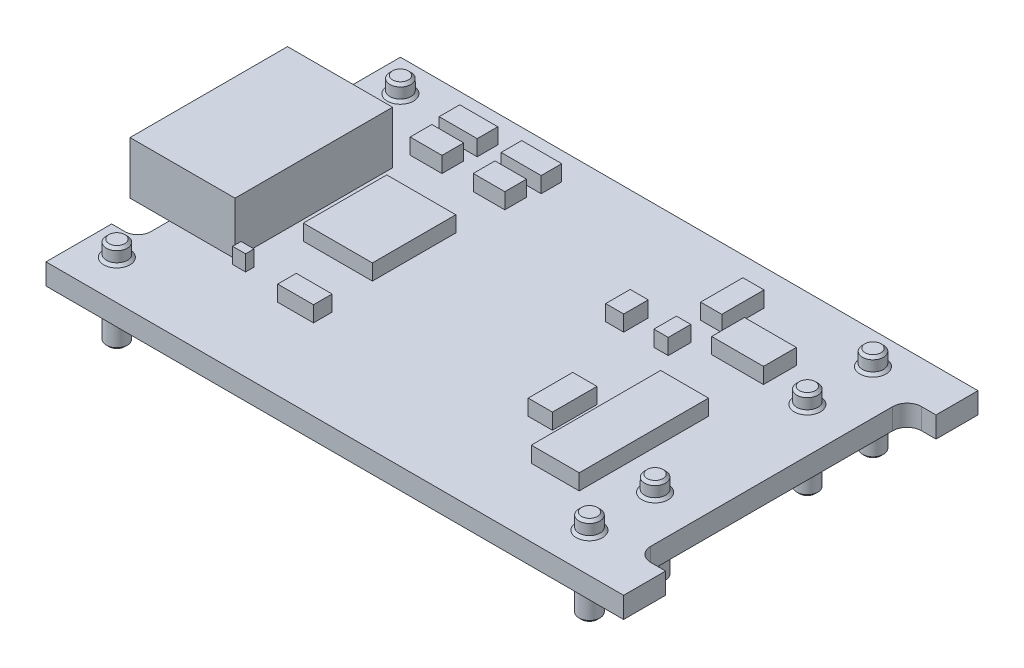
SolidWorks part; units mm, degrees
ref_plane "Front Plane" through (0, 0, 0) normal (0, 0, 1) x (1, 0, 0)
ref_plane "Top Plane" through (0, 0, 0) normal (0, 1, 0) x (1, 0, 0)
ref_plane "Right Plane" through (0, 0, 0) normal (1, 0, 0) x (0, 0, -1)
sketch "Sketch1" plane through (0, 0, 0) normal (0, 1, 0) x (1, 0, 0)
  line L1 (0, 0) -> (27.94, 0)
  line L2 (0, 0) -> (0, 17.145)
  line L3 (0, 17.145) -> (27.94, 17.145)
  line L4 (27.94, 0) -> (27.94, 17.145)
  line L5 (13.97, 17.145) -> (13.97, 0) construction
  line L6 (0, 8.5725) -> (27.94, 8.5725) construction
  point P88 (13.97, 8.5725)
  dimension "D1" = 17.145
  dimension "D2" = 27.94
extrude "Boss-Extrude1" add sketch "Sketch1" along normal blind 1.016
sketch "Sketch2" plane through (0, 1.016, 0) normal (0, 1, 0) x (1, 0, 0)
  line L0 (27.94, 17.145) -> (27.94, 15.113)
  line L1 (27.94, 0) -> (27.94, 17.145) construction
  line L2 (27.94, 0) -> (27.94, 2.032)
  line L3 (0, 17.145) -> (0, 13.843)
  line L4 (27.94, 2.032) -> (26.543, 2.032)
  line L5 (27.94, 2.032) -> (27.94, 15.113)
  line L6 (27.94, 15.113) -> (26.543, 15.113)
  line L7 (26.543, 2.032) -> (26.543, 15.113)
  line L8 (27.2415, 15.113) -> (27.2415, 2.032) construction
  line L9 (27.94, 8.5725) -> (26.543, 8.5725) construction
  line L10 (0, 17.145) -> (0, 0) construction
  line L11 (0, 0) -> (0, 3.302)
  line L13 (0, 13.843) -> (1.27, 13.843)
  line L14 (0, 13.843) -> (0, 3.175)
  line L15 (0, 3.175) -> (1.27, 3.175)
  line L16 (1.27, 13.843) -> (1.27, 3.175)
  line L17 (0.635, 3.175) -> (0.635, 13.843) construction
  line L18 (0, 8.509) -> (1.27, 8.509) construction
  arc A0 (27.2415, 15.113) -> (26.543, 14.4145) centre (27.2415, 14.4145) ccw
  arc A1 (27.2415, 2.032) -> (26.543, 2.6934) centre (27.2229, 2.7119) cw
  arc A2 (0.6501, 13.843) -> (1.27, 13.196) centre (0.6365, 13.2095) cw
  arc A3 (1.27, 3.7929) -> (0.635, 3.175) centre (0.6435, 3.8015) cw
  point P130 (0.635, 8.509)
  point P187 (27.2415, 8.5725)
  line M3 (0, 17.145) -> (0, 0)
  line M5 (27.94, 0) -> (27.94, 17.145)
  dimension "D4" = 3.302
  dimension "D1" = 2.032
  dimension "D2" = 2.032
  dimension "D3" = 1.397
  dimension "D5" = 3.302
  dimension "D6" = 10.668
  dimension "D7" = 1.27
extrude "Cut-Extrude1" cut sketch "Sketch2" against normal blind 1.016 contours A3 L16 A2 L13 L15 M3 | A1 L4 L6 A0 L7 M5
sketch "Sketch3" plane through (0, 1.016, 0) normal (0, 1, 0) x (1, 0, 0)
  line L0 (24.384, 15.621) -> (24.384, 12.446)
  line L1 (0, 17.145) -> (3.048, 17.145)
  line L2 (0, 17.145) -> (0, 14.097)
  line L3 (0, 14.097) -> (3.048, 14.097)
  line L4 (3.048, 17.145) -> (3.048, 14.097)
  line L5 (1.524, 14.097) -> (1.524, 17.145) construction
  line L6 (0, 15.621) -> (3.048, 15.621) construction
  line L7 (0, 0) -> (3.048, 0)
  line L8 (0, 0) -> (0, 3.81)
  line L9 (0, 3.81) -> (3.048, 3.81)
  line L10 (3.048, 0) -> (3.048, 3.81)
  line L11 (1.524, 3.81) -> (1.524, 0) construction
  line L12 (0, 1.905) -> (3.048, 1.905) construction
  line L13 (27.94, 17.145) -> (24.384, 17.145)
  line L14 (27.94, 17.145) -> (27.94, 15.621)
  line L15 (27.94, 15.621) -> (24.384, 15.621)
  line L16 (24.384, 17.145) -> (24.384, 15.621)
  line L17 (26.162, 15.621) -> (26.162, 17.145) construction
  line L18 (27.94, 16.383) -> (24.384, 16.383) construction
  line L19 (24.384, 1.905) -> (24.384, 5.08)
  line L20 (27.94, 0) -> (24.384, 0)
  line L21 (27.94, 0) -> (27.94, 1.905)
  line L22 (27.94, 1.905) -> (24.384, 1.905)
  line L23 (24.384, 0) -> (24.384, 1.905)
  line L24 (26.162, 1.905) -> (26.162, 0) construction
  line L25 (27.94, 0.9525) -> (24.384, 0.9525) construction
  circle A0 centre (1.524, 15.621) radius 0.508
  circle A1 centre (1.524, 1.905) radius 0.508
  circle A2 centre (24.384, 15.621) radius 0.508
  circle A3 centre (24.384, 12.446) radius 0.508
  circle A4 centre (24.384, 1.905) radius 0.508
  circle A5 centre (24.384, 5.08) radius 0.508
  point P89 (26.162, 0.9525)
  point P112 (26.162, 16.383)
  point P188 (1.524, 1.905)
  point P260 (1.524, 15.621)
  dimension "D1" = 1.016
  dimension "D3" = 1.016
  dimension "D6" = 1.016
  dimension "D8" = 1.016
  dimension "D11" = 1.016
  dimension "D13" = 1.016
  dimension "D2" = 3.81
  dimension "D4" = 1.524
  dimension "D5" = 3.556
  dimension "D7" = 3.175
  dimension "D9" = 1.905
  dimension "D10" = 3.556
  dimension "D12" = 3.175
extrude "Boss-Extrude2" add sketch "Sketch3" against normal blind 3.556 and the other way blind 0.762
chamfer "Chamfer1" distance 0.127 angle 45 24 edges at (24.384, -2.54, -15.113) (24.384, 0, -16.129) (24.384, -2.54, -11.938) (24.384, 0, -12.954) (24.384, -2.54, -4.572) (24.384, 0, -5.588) (24.384, -2.54, -1.397) (24.384, 0, -2.413) (24.384, 1.016, -2.413) (24.384, 1.778, -1.397) (24.384, 1.016, -5.588) (24.384, 1.778, -4.572) (24.384, 1.016, -12.954) (24.384, 1.778, -11.938) (24.384, 1.016, -16.129) (24.384, 1.778, -15.113) (1.524, 1.016, -16.129) (1.524, 1.778, -15.113) (1.524, -2.54, -15.113) (1.524, 0, -16.129) (1.524, -2.54, -1.397) (1.524, 0, -2.413) (1.524, 1.016, -2.413) (1.524, 1.778, -1.397)
sketch "Sketch4" plane through (0, 1.016, 0) normal (0, 1, 0) x (1, 0, 0)
  line L1 (4.1903, 15.8238) -> (6.0303, 15.8238)
  line L2 (4.1903, 15.8238) -> (4.1903, 14.8288)
  line L3 (4.1903, 14.8288) -> (6.0303, 14.8288)
  line L4 (6.0303, 15.8238) -> (6.0303, 14.8288)
  line L5 (5.1103, 14.8288) -> (5.1103, 15.8238) construction
  line L6 (4.1903, 15.3263) -> (6.0303, 15.3263) construction
  line L7 (7.1889, 15.8238) -> (9.1244, 15.8238)
  line L8 (7.1889, 15.8238) -> (7.1889, 14.8288)
  line L9 (7.1889, 14.8288) -> (9.1244, 14.8288)
  line L10 (9.1244, 15.8238) -> (9.1244, 14.8288)
  line L11 (8.1567, 14.8288) -> (8.1567, 15.8238) construction
  line L12 (7.1889, 15.3263) -> (9.1244, 15.3263) construction
  line L13 (4.3402, 14.3245) -> (5.8804, 14.3245)
  line L14 (4.3402, 14.3245) -> (4.3402, 13.275)
  line L15 (4.3402, 13.275) -> (5.8804, 13.275)
  line L16 (5.8804, 14.3245) -> (5.8804, 13.275)
  line L17 (5.1103, 13.275) -> (5.1103, 14.3245) construction
  line L18 (4.3402, 13.7997) -> (5.8804, 13.7997) construction
  line L19 (7.3934, 14.3245) -> (8.92, 14.3245)
  line L20 (7.3934, 14.3245) -> (7.3934, 13.275)
  line L21 (7.3934, 13.275) -> (8.92, 13.275)
  line L22 (8.92, 14.3245) -> (8.92, 13.275)
  line L23 (8.1567, 13.275) -> (8.1567, 14.3245) construction
  line L24 (7.3934, 13.7997) -> (8.92, 13.7997) construction
  line L25 (22.4958, 13.7997) -> (19.9878, 13.7997)
  line L26 (22.4958, 13.7997) -> (22.4958, 12.2118)
  line L27 (22.4958, 12.2118) -> (19.9878, 12.2118)
  line L28 (19.9878, 13.7997) -> (19.9878, 12.2118)
  line L29 (21.2418, 12.2118) -> (21.2418, 13.7997) construction
  line L30 (22.4958, 13.0058) -> (19.9878, 13.0058) construction
  line L31 (18.284, 15.4285) -> (19.3063, 15.4285)
  line L32 (18.284, 15.4285) -> (18.284, 13.384)
  line L33 (18.284, 13.384) -> (19.3063, 13.384)
  line L34 (19.3063, 15.4285) -> (19.3063, 13.384)
  line L35 (18.7951, 13.384) -> (18.7951, 15.4285) construction
  line L36 (18.284, 14.4063) -> (19.3063, 14.4063) construction
  line L37 (18.284, 12.2118) -> (18.9791, 12.2118)
  line L38 (18.284, 12.2118) -> (18.284, 11.1214)
  line L39 (18.284, 11.1214) -> (18.9791, 11.1214)
  line L40 (18.9791, 12.2118) -> (18.9791, 11.1214)
  line L41 (18.6316, 11.1214) -> (18.6316, 12.2118) construction
  line L42 (18.284, 11.6666) -> (18.9791, 11.6666) construction
  line L43 (20.1786, 9.5539) -> (22.4958, 9.5539)
  line L44 (20.1786, 9.5539) -> (20.1786, 3.2976)
  line L45 (20.1786, 3.2976) -> (22.4958, 3.2976)
  line L46 (22.4958, 9.5539) -> (22.4958, 3.2976)
  line L47 (21.3372, 3.2976) -> (21.3372, 9.5539) construction
  line L48 (20.1786, 6.4257) -> (22.4958, 6.4257) construction
  line L49 (18.1341, 7.3458) -> (19.3063, 7.3458)
  line L50 (18.1341, 7.3458) -> (18.1341, 5.1922)
  line L51 (18.1341, 5.1922) -> (19.3063, 5.1922)
  line L52 (19.3063, 7.3458) -> (19.3063, 5.1922)
  line L53 (18.7202, 5.1922) -> (18.7202, 7.3458) construction
  line L54 (18.1341, 6.269) -> (19.3063, 6.269) construction
  line L55 (5.3625, 11.1214) -> (8.7019, 11.1214)
  line L56 (5.3625, 11.1214) -> (5.3625, 7.0868)
  line L57 (5.3625, 7.0868) -> (8.7019, 7.0868)
  line L58 (8.7019, 11.1214) -> (8.7019, 7.0868)
  line L59 (7.0322, 7.0868) -> (7.0322, 11.1214) construction
  line L60 (5.3625, 9.1041) -> (8.7019, 9.1041) construction
  line L61 (4.6264, 4.8105) -> (5.2534, 4.8105)
  line L62 (4.6264, 4.8105) -> (4.6264, 4.4016)
  line L63 (4.6264, 4.4016) -> (5.2534, 4.4016)
  line L64 (5.2534, 4.8105) -> (5.2534, 4.4016)
  line L65 (4.9399, 4.4016) -> (4.9399, 4.8105) construction
  line L66 (4.6264, 4.6061) -> (5.2534, 4.6061) construction
  line L67 (7.298, 4.8105) -> (9.029, 4.8105)
  line L68 (7.298, 4.8105) -> (7.298, 3.9109)
  line L69 (7.298, 3.9109) -> (9.029, 3.9109)
  line L70 (9.029, 4.8105) -> (9.029, 3.9109)
  line L71 (8.1635, 3.9109) -> (8.1635, 4.8105) construction
  line L72 (7.298, 4.3607) -> (9.029, 4.3607) construction
  line L73 (16.0486, 12.2118) -> (16.921, 12.2118)
  line L74 (16.0486, 12.2118) -> (16.0486, 11.026)
  line L75 (16.0486, 11.026) -> (16.921, 11.026)
  line L76 (16.921, 12.2118) -> (16.921, 11.026)
  line L77 (16.4848, 11.026) -> (16.4848, 12.2118) construction
  line L78 (16.0486, 11.6189) -> (16.921, 11.6189) construction
  point P84 (5.1103, 15.3263)
  point P87 (18.6316, 11.6666)
  point P90 (18.7202, 6.269)
  point P99 (5.1103, 13.7997)
  point P104 (18.7951, 14.4063)
  point P116 (8.1567, 13.7997)
  point P134 (4.9399, 4.6061)
  point P159 (8.1635, 4.3607)
  point P164 (16.4848, 11.6189)
  point P185 (8.1567, 15.3263)
  point P188 (21.3372, 6.4257)
  point P240 (21.2418, 13.0058)
  point P245 (7.0322, 9.1041)
extrude "Boss-Extrude4" add sketch "Sketch4" along normal blind 0.762
sketch "Sketch5" plane through (0, 1.016, 0) normal (0, 1, 0) x (1, 0, 0)
  line L1 (0, 17.145) -> (4.445, 17.145)
  line L2 (0, 17.145) -> (0, 12.319)
  line L3 (0, 12.319) -> (4.445, 12.319)
  line L4 (4.445, 17.145) -> (4.445, 12.319)
  line L5 (2.2225, 12.319) -> (2.2225, 17.145) construction
  line L6 (0, 14.732) -> (4.445, 14.732) construction
  line L7 (4.445, 12.319) -> (-0.635, 12.319)
  line L8 (4.445, 12.319) -> (4.445, 4.699)
  line L9 (4.445, 4.699) -> (-0.635, 4.699)
  line L10 (-0.635, 12.319) -> (-0.635, 4.699)
  line L11 (1.905, 4.699) -> (1.905, 12.319) construction
  line L12 (4.445, 8.509) -> (-0.635, 8.509) construction
  point P181 (1.905, 8.509)
  point P200 (2.2225, 14.732)
  dimension "D1" = 4.826
  dimension "D2" = 4.445
  dimension "D3" = 7.62
extrude "Boss-Extrude5" add sketch "Sketch5" along normal blind 2.54 contours L7 L10 L9 L8 L3
